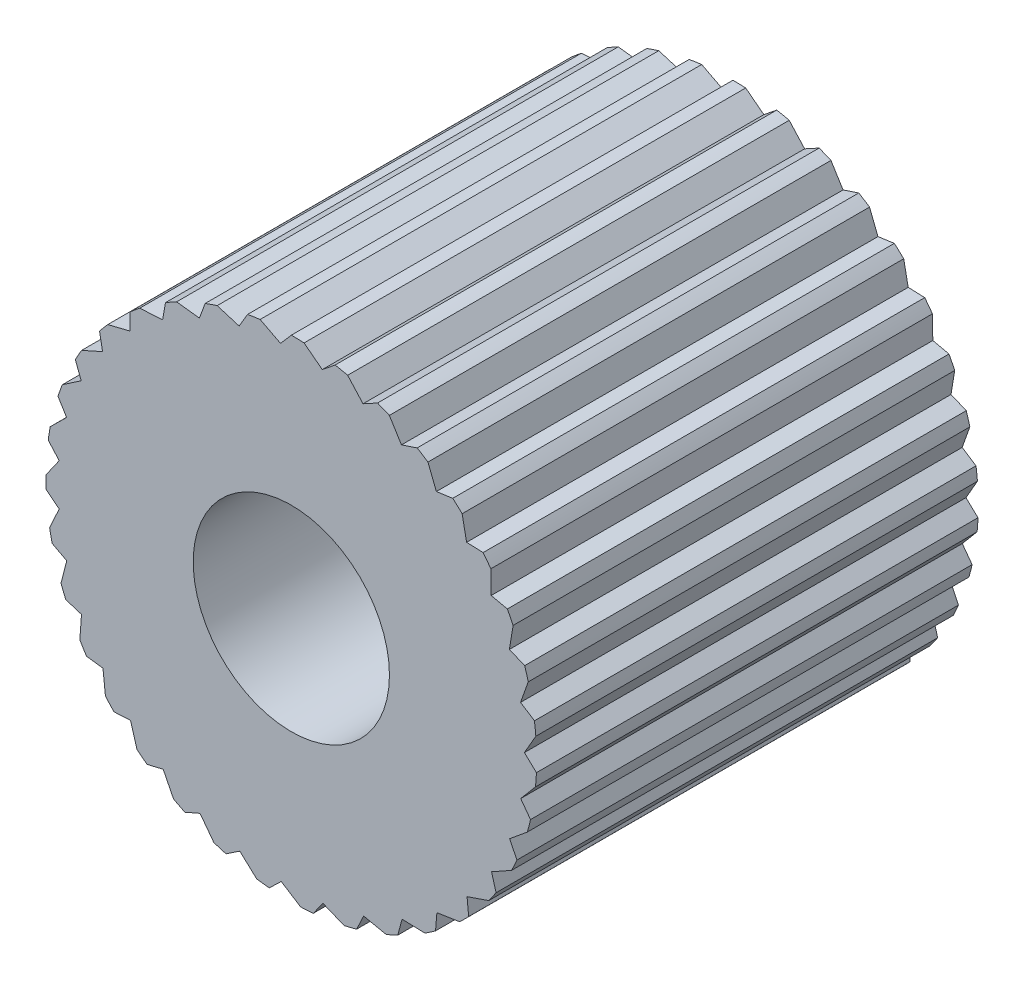
SolidWorks part; units mm, degrees
ref_plane "정면" through (0, 0, 0) normal (0, 0, 1) x (1, 0, 0)
ref_plane "윗면" through (0, 0, 0) normal (0, 1, 0) x (1, 0, 0)
ref_plane "우측면" through (0, 0, 0) normal (1, 0, 0) x (0, 0, -1)
sketch "스케치1" plane through (0, 0, 0) normal (0, 0, 1) x (1, 0, 0)
  circle A0 centre (0, 0) radius 10
  dimension "D1" = 20
extrude "보스-돌출1" add sketch "스케치1" along normal blind 18
sketch "스케치2" plane through (0, 0, 18) normal (0, 0, 1) x (1, 0, 0)
  line L0 (-1.2713, 9.9189) -> (-0.4401, 9.4894)
  line L1 (-0.4401, 9.4894) -> (0, 10)
  line L2 (0.5202, 9.9865) -> (1.2614, 9.4155)
  line L3 (1.2614, 9.4155) -> (1.7856, 9.8393)
  line L4 (2.295, 9.7331) -> (2.9223, 9.039)
  line L5 (2.9223, 9.039) -> (3.5137, 9.3623)
  line L6 (3.9961, 9.1669) -> (4.4893, 8.3719)
  line L7 (4.4893, 8.3719) -> (5.129, 8.5845)
  line L8 (5.5687, 8.306) -> (5.912, 7.4358)
  line L9 (5.912, 7.4358) -> (6.5794, 7.5307)
  line L10 (6.9623, 7.1782) -> (7.1447, 6.2606)
  line L11 (7.1447, 6.2606) -> (7.8183, 6.2349)
  line L12 (8.1321, 5.8197) -> (8.1478, 4.8843)
  line L13 (8.1478, 4.8843) -> (8.806, 4.7387)
  line L14 (9.0406, 4.2741) -> (8.889, 3.3509)
  line L15 (8.889, 3.3509) -> (9.5106, 3.0902)
  line L16 (9.6585, 2.5912) -> (9.3445, 1.7099)
  line L17 (9.3445, 1.7099) -> (9.9095, 1.3423)
  line L18 (9.9659, 0.825) -> (9.4996, 0.0139)
  line L19 (9.4996, 0.0139) -> (9.9899, -0.4486)
  line L20 (9.9531, -0.9678) -> (9.3494, -1.6825)
  line L21 (9.3494, -1.6825) -> (9.7493, -2.2252)
  line L22 (9.6203, -2.7294) -> (8.8987, -3.3249)
  line L23 (8.8987, -3.3249) -> (9.1953, -3.9303)
  line L24 (8.9784, -4.4033) -> (8.1621, -4.8604)
  line L25 (8.1621, -4.8604) -> (8.3457, -5.509)
  line L26 (8.0478, -5.9357) -> (7.163, -6.2397)
  line L27 (7.163, -6.2397) -> (7.2279, -6.9106)
  line L28 (6.8586, -7.2773) -> (5.9338, -7.4184)
  line L29 (5.9338, -7.4184) -> (5.8779, -8.0902)
  line L30 (5.449, -8.385) -> (4.5138, -8.3587)
  line L31 (4.5138, -8.3587) -> (4.3388, -9.0097)
  line L32 (3.8642, -9.2232) -> (2.9488, -9.0304)
  line L33 (2.9488, -9.0304) -> (2.6604, -9.6396)
  line L34 (2.1553, -9.765) -> (1.2889, -9.4118)
  line L35 (1.2889, -9.4118) -> (0.8964, -9.9597)
  line L36 (0.377, -9.9929) -> (-0.4123, -9.4907)
  line L37 (-0.4123, -9.4907) -> (-0.8964, -9.9597)
  line L38 (-1.4133, -9.8996) -> (-2.1003, -9.2645)
  line L39 (-2.1003, -9.2645) -> (-2.6604, -9.6396)
  line L40 (-3.1583, -9.4882) -> (-3.7208, -8.7406)
  line L41 (-3.7208, -8.7406) -> (-4.3388, -9.0097)
  line L42 (-4.8017, -8.7718) -> (-5.2217, -7.9358)
  line L43 (-5.2217, -7.9358) -> (-5.8779, -8.0902)
  line L44 (-6.2908, -7.7734) -> (-6.5548, -6.8759)
  line L45 (-6.5548, -6.8759) -> (-7.2279, -6.9106)
  line L46 (-7.5777, -6.5252) -> (-7.6772, -5.595)
  line L47 (-7.6772, -5.595) -> (-8.3457, -5.509)
  line L48 (-8.621, -5.0673) -> (-8.5528, -4.1342)
  line L49 (-8.5528, -4.1342) -> (-9.1953, -3.9303)
  line L50 (-9.3873, -3.4465) -> (-9.1536, -2.5406)
  line L51 (-9.1536, -2.5406) -> (-9.7493, -2.2252)
  line L52 (-9.8518, -1.715) -> (-9.4601, -0.8654)
  line L53 (-9.4601, -0.8654) -> (-9.9899, -0.4486)
  line L54 (-9.9997, 0.0717) -> (-9.4626, 0.8377)
  line L55 (-9.4626, 0.8377) -> (-9.9095, 1.3423)
  line L56 (-9.8262, 1.8561) -> (-9.161, 2.5138)
  line L57 (-9.161, 2.5138) -> (-9.5106, 3.0902)
  line L58 (-9.3369, 3.5808) -> (-8.5649, 4.1092)
  line L59 (-8.5649, 4.1092) -> (-8.806, 4.7387)
  line L60 (-8.5475, 5.1904) -> (-7.6935, 5.5725)
  line L61 (-7.6935, 5.5725) -> (-7.8183, 6.2349)
  line L62 (-7.4834, 6.6332) -> (-6.5749, 6.8567)
  line L63 (-6.5749, 6.8567) -> (-6.5794, 7.5307)
  line L64 (-6.1787, 7.8628) -> (-5.2449, 7.9205)
  line L65 (-5.2449, 7.9205) -> (-5.129, 8.5845)
  line L66 (-4.6754, 8.8397) -> (-3.7464, 8.7297)
  line L67 (-3.7464, 8.7297) -> (-3.5137, 9.3623)
  line L68 (-3.0219, 9.5325) -> (-2.1274, 9.2583)
  line L69 (-2.1274, 9.2583) -> (-1.7856, 9.8393)
  circle A0 centre (0, 0) radius 10 construction
  arc A1 (0, 10) -> (-1.2713, 9.9189) centre (-0.5942, 9.3106) ccw
  arc A2 (1.7856, 9.8393) -> (0.5202, 9.9865) centre (1.0778, 9.2671) ccw
  arc A3 (3.5137, 9.3623) -> (2.295, 9.7331) centre (2.7152, 8.9257) ccw
  arc A4 (5.129, 8.5845) -> (3.9961, 9.1669) centre (4.2653, 8.2974) ccw
  arc A5 (6.5794, 7.5307) -> (5.5687, 8.306) centre (5.6783, 7.4025) ccw
  arc A6 (7.8183, 6.2349) -> (6.9623, 7.1782) centre (6.9088, 6.2696) ccw
  arc A7 (8.806, 4.7387) -> (8.1321, 5.8197) centre (7.9173, 4.9353) ccw
  arc A8 (9.5106, 3.0902) -> (9.0406, 4.2741) centre (8.6713, 3.4423) ccw
  arc A9 (9.9095, 1.3423) -> (9.6585, 2.5912) centre (9.1466, 1.8386) ccw
  arc A10 (9.9899, -0.4486) -> (9.9659, 0.825) centre (9.3279, 0.1759) ccw
  arc A11 (9.7493, -2.2252) -> (9.9531, -0.9678) centre (9.2094, -1.4925) ccw
  arc A12 (9.1953, -3.9303) -> (9.6203, -2.7294) centre (8.7949, -3.1129) ccw
  arc A13 (8.3457, -5.509) -> (8.9784, -4.4033) centre (8.0977, -4.6333) ccw
  arc A14 (7.2279, -6.9106) -> (8.0478, -5.9357) centre (7.1403, -6.0047) ccw
  arc A15 (5.8779, -8.0902) -> (6.8586, -7.2773) centre (5.9534, -7.1831) ccw
  arc A16 (4.3388, -9.0097) -> (5.449, -8.385) centre (4.5751, -8.1307) ccw
  arc A17 (2.6604, -9.6396) -> (3.8642, -9.2232) centre (3.0498, -8.817) ccw
  arc A18 (0.8964, -9.9597) -> (2.1553, -9.765) centre (1.4264, -9.2198) ccw
  arc A19 (-0.8964, -9.9597) -> (0.377, -9.9929) centre (-0.2428, -9.3264) ccw
  arc A20 (-2.6604, -9.6396) -> (-1.4133, -9.8996) centre (-1.9042, -9.1331) ccw
  arc A21 (-4.3388, -9.0097) -> (-3.1583, -9.4882) centre (-3.5043, -8.6464) ccw
  arc A22 (-5.8779, -8.0902) -> (-4.8017, -8.7718) centre (-4.9919, -7.8817) ccw
  arc A23 (-7.2279, -6.9106) -> (-6.2908, -7.7734) centre (-6.319, -6.8637) ccw
  arc A24 (-8.3457, -5.509) -> (-7.5777, -6.5252) centre (-7.443, -5.6251) ccw
  arc A25 (-9.1953, -3.9303) -> (-8.621, -5.0673) centre (-8.3278, -4.2057) ccw
  arc A26 (-9.7493, -2.2252) -> (-9.3873, -3.4465) centre (-8.9449, -2.6511) ccw
  arc A27 (-9.9899, -0.4486) -> (-9.8518, -1.715) centre (-9.2746, -1.0113) ccw
  arc A28 (-9.9095, 1.3423) -> (-9.9997, 0.0717) centre (-9.3061, 0.6609) ccw
  arc A29 (-9.5106, 3.0902) -> (-9.8262, 1.8561) centre (-9.0385, 2.312) ccw
  arc A30 (-8.806, 4.7387) -> (-9.3369, 3.5808) centre (-8.4804, 3.8887) ccw
  arc A31 (-7.8183, 6.2349) -> (-8.5475, 5.1904) centre (-7.6498, 5.3405) ccw
  arc A32 (-6.5794, 7.5307) -> (-7.4834, 6.6332) centre (-6.5733, 6.6206) ccw
  arc A33 (-5.129, 8.5845) -> (-6.1787, 7.8628) centre (-5.2855, 7.6879) ccw
  arc A34 (-3.5137, 9.3623) -> (-4.6754, 8.8397) centre (-3.8278, 8.5081) ccw
  arc A35 (-1.7856, 9.8393) -> (-3.0219, 9.5325) centre (-2.2471, 9.0549) ccw
  point P144 (0, 0)
  dimension "D1" = 35
extrude "컷-돌출1" cut sketch "스케치2" against normal blind 18
sketch "스케치3" plane through (0, 0, 18) normal (0, 0, 1) x (1, 0, 0)
  circle A0 centre (0, 0) radius 4
  dimension "D1" = 8
extrude "컷-돌출2" cut sketch "스케치3" against normal blind 18
